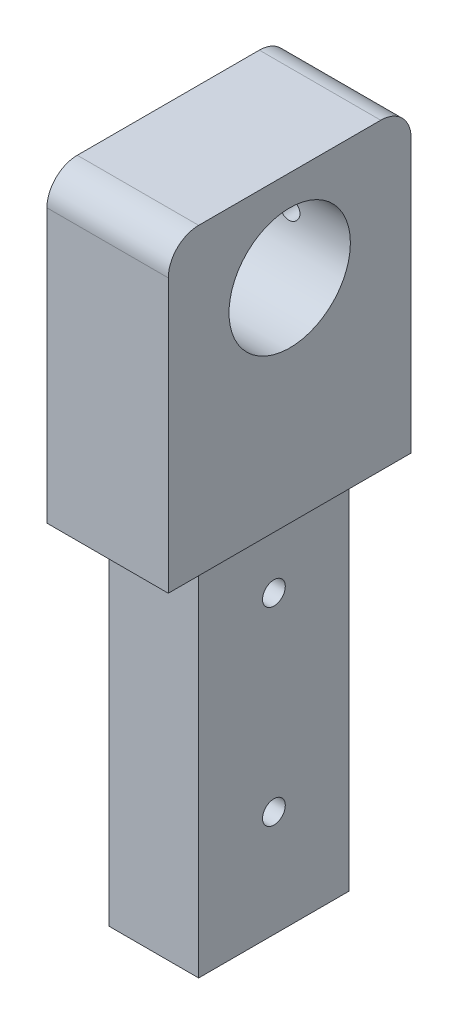
SolidWorks part; units mm, degrees
material "6061-T6 (SS)"
ref_plane "Front Plane" through (0, 0, 0) normal (0, 0, 1) x (1, 0, 0)
ref_plane "Top Plane" through (0, 0, 0) normal (0, 1, 0) x (1, 0, 0)
ref_plane "Right Plane" through (0, 0, 0) normal (1, 0, 0) x (0, 0, -1)
sketch "Sketch2" plane through (0, 0, 0) normal (0, 1, 0) x (1, 0, 0)
  line L1 (-10.414, -16.764) -> (10.414, -16.764)
  line L2 (-10.414, -16.764) -> (-10.414, 16.764)
  line L3 (-10.414, 16.764) -> (10.414, 16.764)
  line L4 (10.414, -16.764) -> (10.414, 16.764)
  line L5 (-10.414, -16.764) -> (10.414, 16.764) construction
  line L6 (-10.414, 16.764) -> (10.414, -16.764) construction
  point P0 (0, 0)
  dimension "D1" = 20.828
  dimension "D2" = 33.528
extrude "Boss-Extrude1" add sketch "Sketch2" along normal blind 76.2
sketch "Sketch3" plane through (0, 76.2, 0) normal (0, 1, 0) x (1, 0, 0)
  line L1 (-12.7, -25.4) -> (12.7, -25.4)
  line L2 (-12.7, -25.4) -> (-12.7, 25.4)
  line L3 (-12.7, 25.4) -> (12.7, 25.4)
  line L4 (12.7, -25.4) -> (12.7, 25.4)
  line L5 (-12.7, -25.4) -> (12.7, 25.4) construction
  line L6 (-12.7, 25.4) -> (12.7, -25.4) construction
  point P0 (0, 0)
  dimension "D1" = 25.4
  dimension "D2" = 50.8
extrude "Boss-Extrude2" add sketch "Sketch3" along normal blind 63.5
fillet "Fillet1" radius 6.35 2 edges at (0, 139.7, -25.4) (0, 139.7, 25.4)
sketch "Sketch4" plane through (12.7, 0, 0) normal (1, 0, 0) x (0, 0, -1)
  line L0 (-25.4, 76.2) -> (25.4, 76.2) construction
  circle A0 centre (0, 120.65) radius 12.7
  dimension "D1" = 25.4
  dimension "D2" = 44.45
extrude "Cut-Extrude1" cut sketch "Sketch4" against normal through all
sketch "Sketch5" plane through (0, 0, -25.4) normal (0, 0, -1) x (-1, 0, 0)
  circle A0 centre (0, 120.65) radius 2.1526
  dimension "D1" = 4.3053
extrude "Cut-Extrude2" cut sketch "Sketch5" against normal up to surface (12.7 mm away) up to face at (-12.7, 120.65, -12.7)
sketch "Sketch6" plane through (0, 0, 0) normal (0, -1, 0) x (1, 0, 0)
  line L0 (-10.414, 16.764) -> (-10.414, -16.764)
  line L1 (-10.414, -16.764) -> (10.414, -16.764)
  line L2 (10.414, -16.764) -> (10.414, 16.764)
  line L3 (10.414, 16.764) -> (-10.414, 16.764)
  line L4 (0, 0) -> (0, 15.875)
  line L5 (0, 15.875) -> (-9.525, 15.875)
  line L6 (-9.525, 15.875) -> (-9.525, -15.875)
  line L7 (-9.525, -15.875) -> (9.525, -15.875)
  line L8 (9.525, -15.875) -> (9.525, 15.875)
  line L9 (9.525, 15.875) -> (0, 15.875)
  line L10 (0, 15.875) -> (9.525, 15.875)
  line L11 (10.414, -16.764) -> (10.414, 16.764)
  line L12 (-10.414, 16.764) -> (10.414, 16.764)
  line L13 (0, 0) -> (0, -15.748)
  line L14 (0, -15.748) -> (9.398, -15.748)
  line L15 (0, 0) -> (0, 15.748)
  line L16 (0, 15.748) -> (-9.398, 15.748)
  line L18 (-9.398, 15.748) -> (9.398, 15.748)
  line L19 (-9.398, 15.748) -> (-9.398, -15.748)
  line L20 (-9.398, -15.748) -> (9.398, -15.748)
  line L21 (9.398, 15.748) -> (9.398, -15.748)
extrude "Cut-Extrude3" cut sketch "Sketch6" along direction (0, -1, 0) on the side against the normal up to surface (76.2 mm away)
sketch "Sketch7" plane through (9.398, 0, 0) normal (1, 0, 0) x (0, 0, -1)
  line L0 (-19.05, 76.2) -> (19.05, 76.2)
  line L1 (-19.05, 76.2) -> (-19.05, 18.0904)
  line L2 (-19.05, 18.0904) -> (19.05, 18.0904)
  line L3 (19.05, 76.2) -> (19.05, 18.0904)
  line L4 (-19.05, 76.2) -> (0, 76.2)
  line L5 (0, 76.2) -> (20.4747, 76.2)
  line L6 (-15.748, 0) -> (-15.748, 76.2)
  line L7 (-15.748, 76.2) -> (0, 76.2)
  line L8 (-25.4, 76.2) -> (25.4, 76.2) construction
  line L9 (0, 76.2) -> (15.748, 76.2)
  circle A0 centre (0, 61.9125) radius 2.3813
  circle A1 centre (0, 22.225) radius 2.3813
extrude "Cut-Extrude4" cut sketch "Sketch7" against normal blind 78.74 contours A0 | A1
